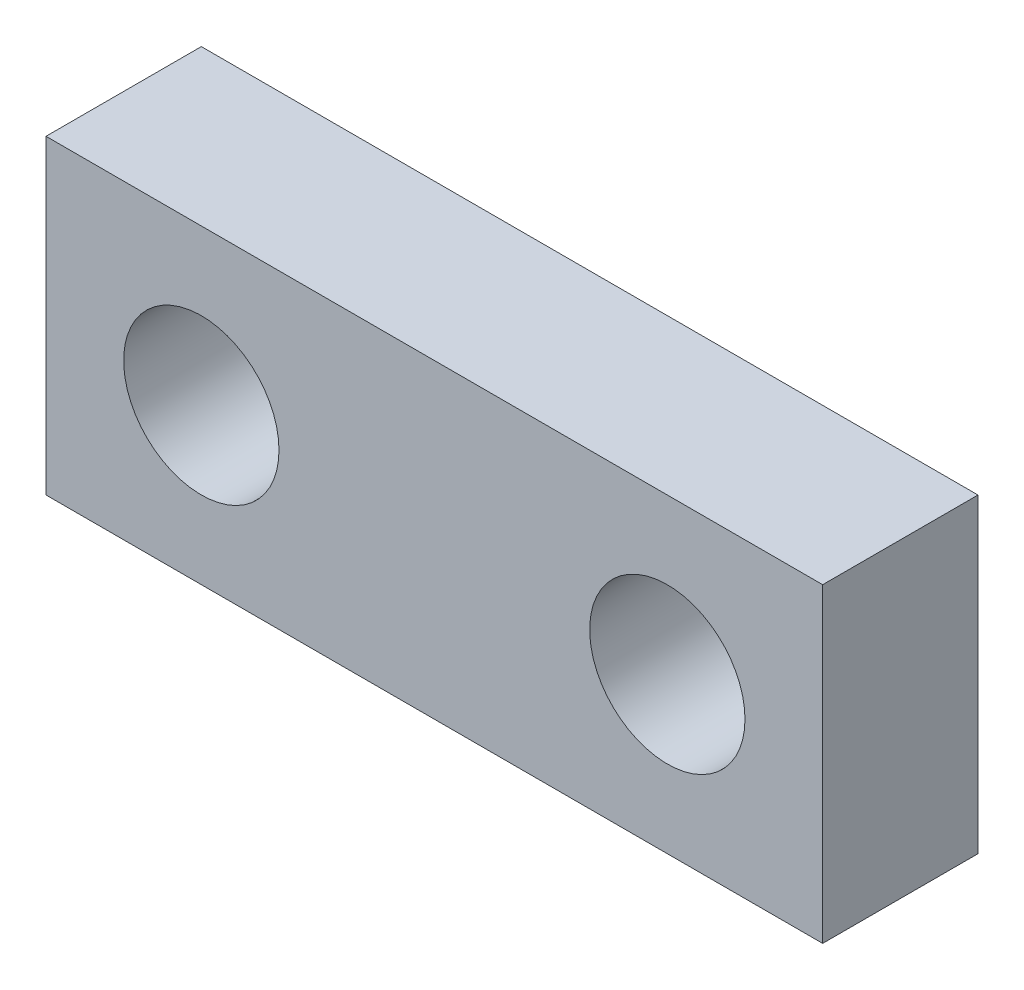
SolidWorks part; units mm, degrees
ref_plane "Front Plane" through (0, 0, 0) normal (0, 0, 1) x (1, 0, 0)
ref_plane "Top Plane" through (0, 0, 0) normal (0, 1, 0) x (1, 0, 0)
ref_plane "Right Plane" through (0, 0, 0) normal (1, 0, 0) x (0, 0, -1)
sketch "Sketch1" plane through (0, 0, 0) normal (0, 0, 1) x (1, 0, 0)
  line L1 (0, 0) -> (-25, 0)
  line L2 (0, 0) -> (0, 10)
  line L3 (0, 10) -> (-25, 10)
  line L4 (-25, 0) -> (-25, 10)
  circle A0 centre (-20, 5) radius 2.5
  circle A1 centre (-5, 5) radius 2.5
  dimension "D1" = 5
  dimension "D2" = 5
  dimension "D3" = 25
  dimension "D4" = 15
  dimension "D5" = 5
  dimension "D6" = 0
  dimension "D7" = 10
  dimension "D8" = 5
extrude "Boss-Extrude1" add sketch "Sketch1" along normal blind 5
